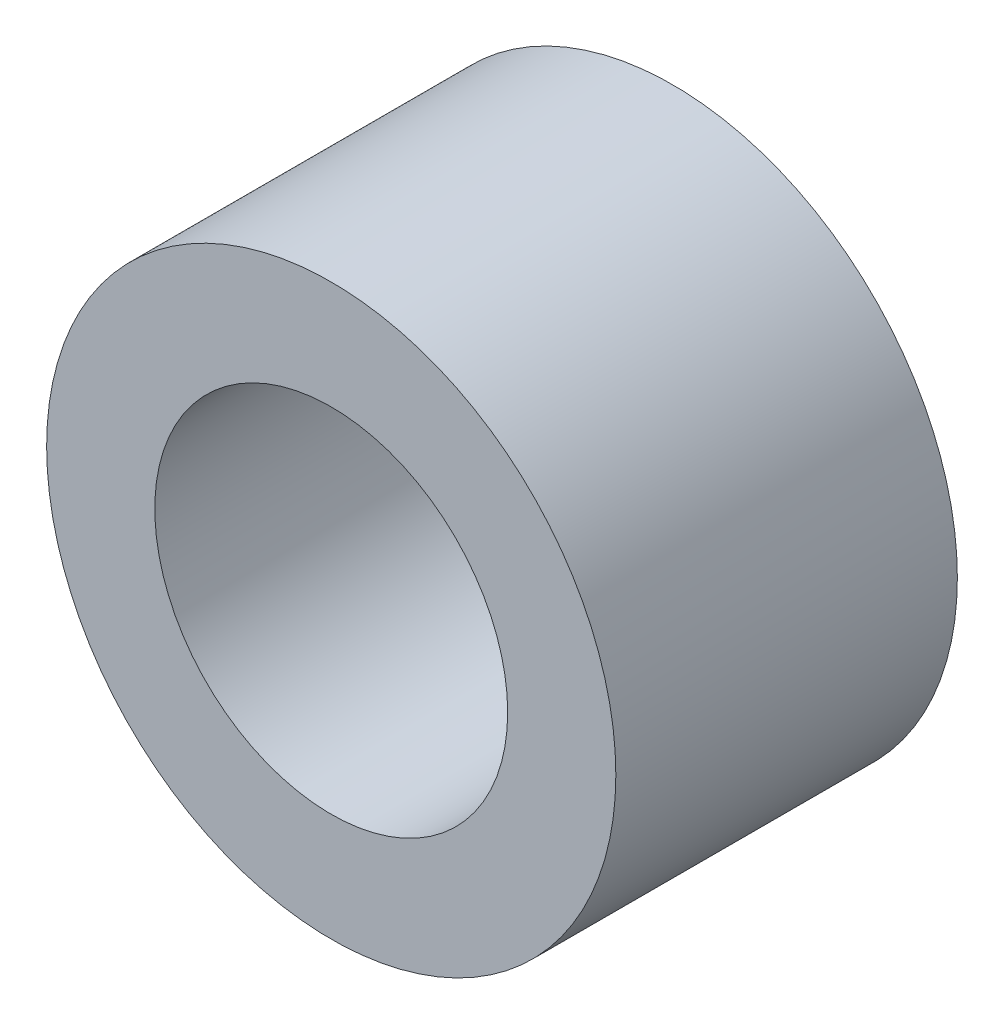
SolidWorks part; units mm, degrees
ref_plane "Front Plane" through (0, 0, 0) normal (0, 0, 1) x (1, 0, 0)
ref_plane "Top Plane" through (0, 0, 0) normal (0, 1, 0) x (1, 0, 0)
ref_plane "Right Plane" through (0, 0, 0) normal (1, 0, 0) x (0, 0, -1)
sketch "Sketch1" plane through (0, 0, 0) normal (0, 0, 1) x (1, 0, 0)
  line L3 (0, 0) -> (0, 5) construction
  circle A0 centre (0, 0) radius 3.1
  circle A1 centre (0, 0) radius 5
  dimension "D1" = 6.2
  dimension "D2" = 10
extrude "Boss-Extrude1" add sketch "Sketch1" along normal blind 6
